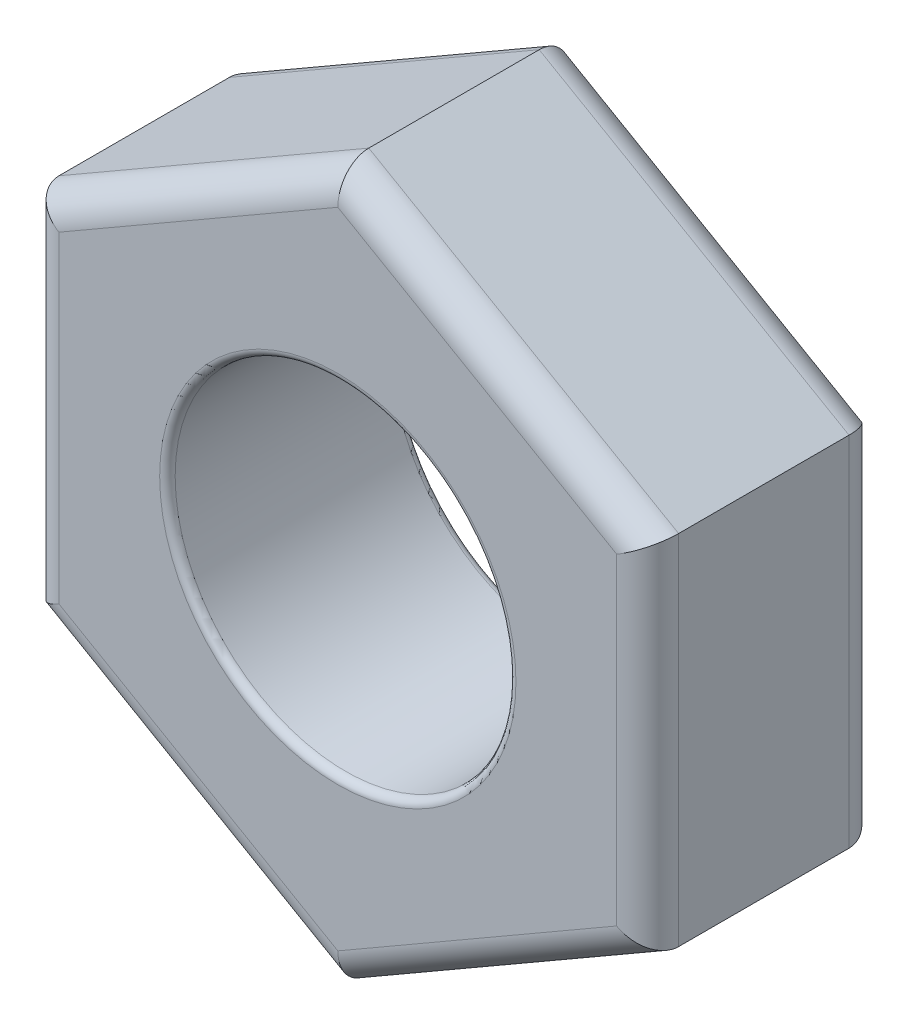
SolidWorks part; units mm, degrees
ref_plane "前视基准面" through (0, 0, 0) normal (0, 0, 1) x (1, 0, 0)
ref_plane "上视基准面" through (0, 0, 0) normal (0, 1, 0) x (1, 0, 0)
ref_plane "右视基准面" through (0, 0, 0) normal (1, 0, 0) x (0, 0, -1)
sketch "草图1" plane through (0, 0, 0) normal (0, 0, 1) x (1, 0, 0)
  line L1 (0, -23.094) -> (20, -11.547)
  line L2 (20, -11.547) -> (20, 11.547)
  line L3 (20, 11.547) -> (0, 23.094)
  line L4 (0, 23.094) -> (-20, 11.547)
  line L5 (-20, 11.547) -> (-20, -11.547)
  line L6 (-20, -11.547) -> (0, -23.094)
  circle A0 centre (0, 0) radius 20 construction
  circle A1 centre (0, 0) radius 11
  dimension "D1" = 22
  dimension "D2" = 40
extrude "凸台-拉伸1" add sketch "草图1" along normal blind 15
fillet "圆角1" radius 2 12 edges at (10, -17.3205, 0) (-10, -17.3205, 0) (-20, 0, 0) (-10, 17.3205, 0) (10, 17.3205, 0) (20, 0, 0) (20, 0, 15) (10, -17.3205, 15) (-10, -17.3205, 15) (-20, 0, 15) (-10, 17.3205, 15) (10, 17.3205, 15)
fillet "圆角2" radius 0.5 2 edges at (11, 0, 0) (11, 0, 15)
